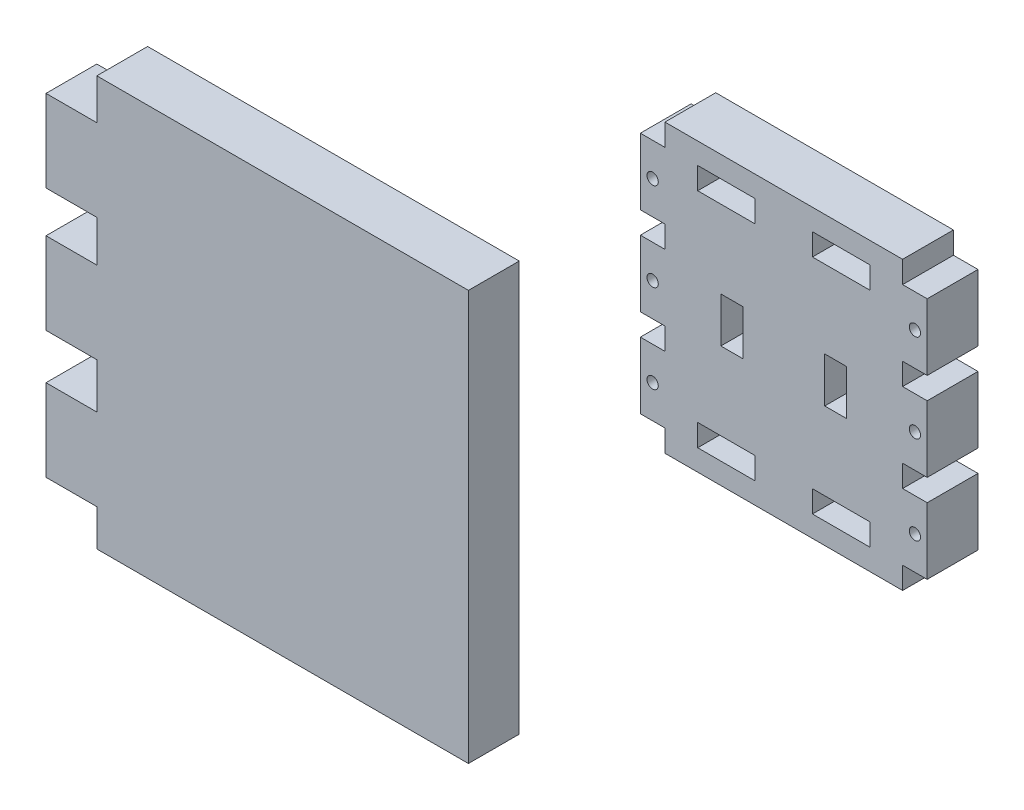
SolidWorks part; units mm, degrees
ref_plane "Front Plane" through (0, 0, 0) normal (0, 0, 1) x (1, 0, 0)
ref_plane "Top Plane" through (0, 0, 0) normal (0, 1, 0) x (1, 0, 0)
ref_plane "Right Plane" through (0, 0, 0) normal (1, 0, 0) x (0, 0, -1)
sketch "Model" plane through (0, 0, 0) normal (0, 0, 1) x (1, 0, 0)
  line L0 (122.2964, 159.5451) -> (122.2964, 89.5451) construction
  line L1 (93.2964, 89.5451) -> (151.2964, 89.5451)
  line L2 (93.2964, 89.5451) -> (93.2964, 94.8951)
  line L3 (93.2964, 159.5451) -> (151.2964, 159.5451)
  line L4 (151.2964, 89.5451) -> (151.2964, 94.8951)
  line L5 (151.2964, 124.5451) -> (75.8907, 124.5451) construction
  line L6 (90.2964, 154.1951) -> (90.2964, 137.9951) construction
  line L7 (101.2964, 154.3751) -> (115.2964, 154.3751)
  line L8 (101.2964, 154.3751) -> (101.2964, 149.0251)
  line L9 (101.2964, 149.0251) -> (115.2964, 149.0251)
  line L10 (115.2964, 154.3751) -> (115.2964, 149.0251)
  line L11 (93.2964, 154.1951) -> (87.2964, 154.1951)
  line L12 (157.2964, 146.0951) -> (151.2964, 146.0951) construction
  line L13 (93.2964, 137.9951) -> (87.2964, 137.9951)
  line L14 (87.2964, 154.1951) -> (87.2964, 137.9951)
  line L15 (87.2964, 146.0951) -> (93.2964, 146.0951) construction
  line L16 (93.2964, 154.1951) -> (93.2964, 159.5451)
  line L17 (154.2964, 154.1951) -> (154.2964, 137.9951) construction
  line L18 (157.2964, 154.1951) -> (157.2964, 137.9951)
  line L19 (151.2964, 137.9951) -> (157.2964, 137.9951)
  line L20 (151.2964, 154.1951) -> (157.2964, 154.1951)
  line L21 (129.2964, 154.3751) -> (129.2964, 149.0251)
  line L22 (143.2964, 149.0251) -> (129.2964, 149.0251)
  line L23 (143.2964, 154.3751) -> (143.2964, 149.0251)
  line L24 (143.2964, 154.3751) -> (129.2964, 154.3751)
  line L25 (154.2964, 94.8951) -> (154.2964, 111.0951) construction
  line L26 (87.2964, 102.9951) -> (93.2964, 102.9951) construction
  line L27 (157.2964, 102.9951) -> (151.2964, 102.9951) construction
  line L28 (90.2964, 94.8951) -> (90.2964, 111.0951) construction
  line L29 (143.2964, 94.7151) -> (129.2964, 94.7151)
  line L30 (143.2964, 94.7151) -> (143.2964, 100.0651)
  line L31 (143.2964, 100.0651) -> (129.2964, 100.0651)
  line L32 (129.2964, 94.7151) -> (129.2964, 100.0651)
  line L33 (151.2964, 94.8951) -> (157.2964, 94.8951)
  line L34 (151.2964, 111.0951) -> (157.2964, 111.0951)
  line L35 (157.2964, 94.8951) -> (157.2964, 111.0951)
  line L36 (87.2964, 94.8951) -> (87.2964, 111.0951)
  line L37 (93.2964, 111.0951) -> (87.2964, 111.0951)
  line L38 (93.2964, 94.8951) -> (87.2964, 94.8951)
  line L39 (115.2964, 94.7151) -> (115.2964, 100.0651)
  line L40 (101.2964, 100.0651) -> (115.2964, 100.0651)
  line L41 (101.2964, 94.7151) -> (101.2964, 100.0651)
  line L42 (101.2964, 94.7151) -> (115.2964, 94.7151)
  line L43 (93.2964, 111.0951) -> (93.2964, 116.4451)
  line L44 (151.2964, 111.0951) -> (151.2964, 116.4451)
  line L45 (151.2964, 154.1951) -> (151.2964, 159.5451)
  line L46 (87.2964, 124.5451) -> (93.2964, 124.5451) construction
  line L47 (93.2964, 132.6451) -> (87.2964, 132.6451)
  line L48 (137.6464, 130.0451) -> (132.2964, 119.0451) construction
  line L49 (93.2964, 116.4451) -> (87.2964, 116.4451)
  line L50 (87.2964, 132.6451) -> (87.2964, 116.4451)
  line L51 (90.2964, 132.6451) -> (90.2964, 116.4451) construction
  line L52 (93.2964, 132.6451) -> (93.2964, 137.9951)
  line L53 (106.9464, 119.0451) -> (112.2964, 119.0451)
  line L54 (106.9464, 119.0451) -> (106.9464, 130.0451)
  line L55 (106.9464, 130.0451) -> (112.2964, 130.0451)
  line L56 (112.2964, 119.0451) -> (112.2964, 130.0451)
  line L57 (106.9464, 119.0451) -> (112.2964, 130.0451) construction
  line L58 (106.9464, 130.0451) -> (112.2964, 119.0451) construction
  line L59 (137.6464, 119.0451) -> (132.2964, 130.0451) construction
  line L60 (154.2964, 132.6451) -> (154.2964, 116.4451) construction
  line L61 (157.2964, 124.5451) -> (151.2964, 124.5451) construction
  line L62 (132.2964, 119.0451) -> (132.2964, 130.0451)
  line L63 (137.6464, 130.0451) -> (132.2964, 130.0451)
  line L64 (137.6464, 119.0451) -> (137.6464, 130.0451)
  line L65 (137.6464, 119.0451) -> (132.2964, 119.0451)
  line L66 (157.2964, 132.6451) -> (157.2964, 116.4451)
  line L67 (151.2964, 116.4451) -> (157.2964, 116.4451)
  line L68 (151.2964, 132.6451) -> (157.2964, 132.6451)
  line L69 (151.2964, 132.6451) -> (151.2964, 137.9951)
  line L70 (-45.3431, 90.0901) -> (-57.7431, 90.0901)
  line L71 (-45.3431, 0) -> (45.3431, 0)
  line L72 (-45.3431, 0) -> (-45.3431, 8.9435)
  line L73 (-45.3431, 100) -> (45.3431, 100)
  line L74 (45.3431, 0) -> (45.3431, 100)
  line L75 (0, 0) -> (0, 100) construction
  line L76 (-45.3431, 60) -> (-45.3431, 70.0901)
  line L77 (-45.3431, 60) -> (-57.7431, 60)
  line L78 (-45.3431, 28.9435) -> (-45.3431, 40)
  line L79 (-45.3431, 40) -> (-57.7431, 40)
  line L80 (-57.7431, 60) -> (-57.7431, 40)
  line L81 (-45.3431, 70.0901) -> (-57.7431, 70.0901)
  line L82 (-57.7431, 90.0901) -> (-57.7431, 70.0901)
  line L83 (-45.3431, 28.9435) -> (-57.7431, 28.9435)
  line L84 (0, 50) -> (-57.7431, 50) construction
  line L85 (-45.3431, 8.9435) -> (-57.7431, 8.9435)
  line L86 (-57.7431, 28.9435) -> (-57.7431, 8.9435)
  line L87 (-45.3431, 90.0901) -> (-45.3431, 100)
  circle A1 centre (90.2964, 146.0951) radius 1.375
  circle A6 centre (154.2964, 146.0951) radius 1.375
  circle A7 centre (154.2964, 102.9951) radius 1.375
  circle A8 centre (90.2964, 102.9951) radius 1.375
  circle A9 centre (90.2964, 124.5451) radius 1.375
  circle A10 centre (154.2964, 124.5451) radius 1.375
  point P84 (109.6214, 124.5451)
  point P102 (134.9714, 124.5451)
  dimension "D23" = 2.75
  dimension "D2" = 58
  dimension "D8" = 5.35
  dimension "D10" = 14
  dimension "D12" = 5.17
  dimension "D14" = 8
  dimension "D19" = 5.35
  dimension "D22" = 5.35
  dimension "D24" = 6
  dimension "D25" = 16.2
  dimension "D26" = 5.35
  dimension "D27" = 11
  dimension "D30" = 13.65
  dimension "D6" = 12.4
  dimension "D7" = 100
  dimension "D9" = 20
  dimension "D4" = 2
  dimension "D5" = 2
extrude "Boss-Extrude1" add sketch "Model" along normal blind 12.4
equation "\"material-thickness\" = 12.4mm"
equation "\"tab-width-large\" = 30mm ' Width of the large version of the Tab"
equation "\"tab-width-small\" = 20mm ' Width of the small version of the Tab"
equation "\"mdfthick\"=5.35"
equation "\"D26@Model\"=\"mdfthick\""
equation "\"D8@Model\"=\"mdfthick\""
equation "\"D19@Model\"=\"mdfthick\""
equation "\"D1@Boss-Extrude1\"=\"material-thickness\""
equation "\"D6@Model\"=\"material-thickness\""
equation "\"D9@Model\"=\"tab-width-small\""
